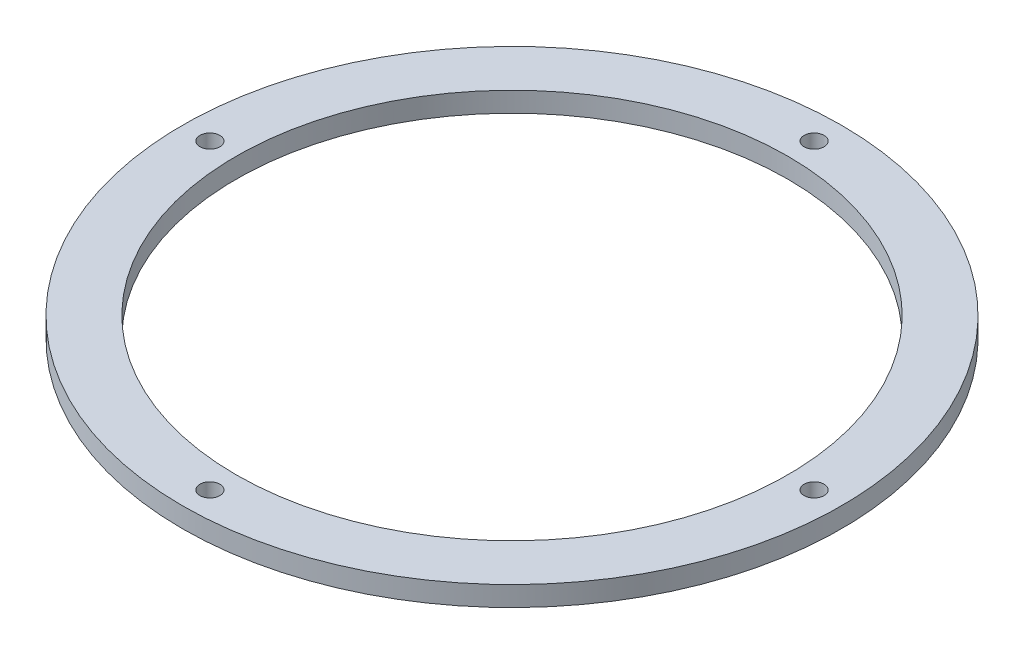
SolidWorks part; units mm, degrees
material "ABS"
ref_plane "前视基准面" through (0, 0, 0) normal (0, 0, 1) x (1, 0, 0)
ref_plane "上视基准面" through (0, 0, 0) normal (0, 1, 0) x (1, 0, 0)
ref_plane "右视基准面" through (0, 0, 0) normal (1, 0, 0) x (0, 0, -1)
other "Configuration Table"
sketch "草图1" plane through (0, 0, 0) normal (0, 1, 0) x (1, 0, 0)
  circle A0 centre (0, 0) radius 72
  circle A1 centre (0, 0) radius 86
  circle A2 centre (0, 78.83) radius 2.6
  circle A3 centre (0, 0) radius 78.83 construction
  circle A4 centre (78.83, 0) radius 2.6
  circle A5 centre (0, -78.83) radius 2.6
  circle A6 centre (-78.83, 0) radius 2.6
  dimension "D1" = 172
  dimension "D2" = 144
  dimension "D3" = 5.2
  dimension "D5" = 157.66
  dimension "D4" = 4
extrude "凸台-拉伸1" add sketch "草图1" along normal blind 5.2
